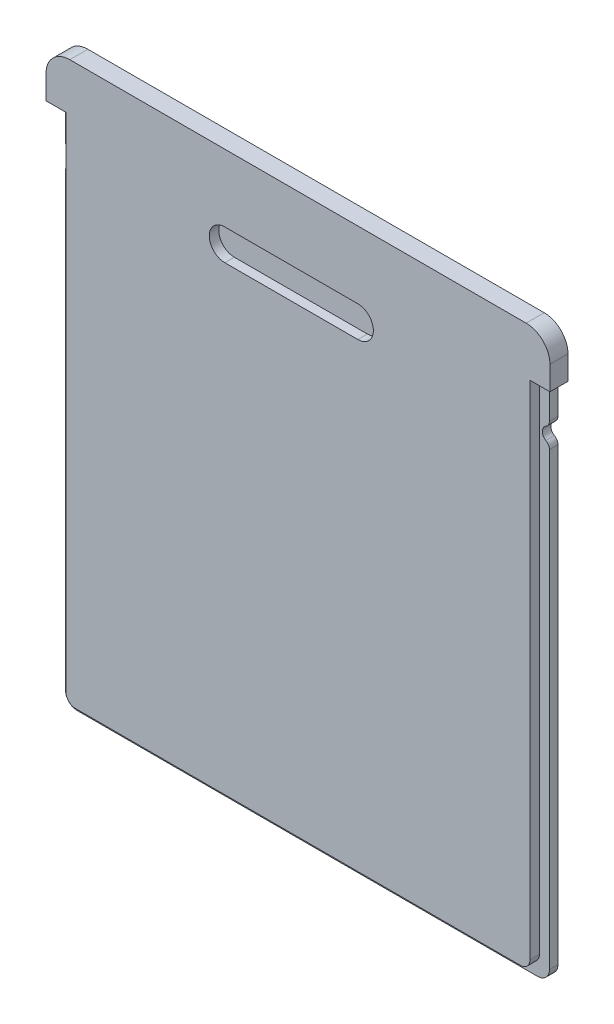
SolidWorks part; units mm, degrees
ref_plane "Front Plane" through (0, 0, 0) normal (0, 0, 1) x (1, 0, 0)
ref_plane "Top Plane" through (0, 0, 0) normal (0, 1, 0) x (1, 0, 0)
ref_plane "Right Plane" through (0, 0, 0) normal (1, 0, 0) x (0, 0, -1)
sketch "Sketch1" plane through (0, 0, 0) normal (0, 0, 1) x (1, 0, 0)
  line L0 (101.8, 109.8) -> (103.9, 109.8)
  line L1 (2.5, 0) -> (99.3, 0)
  line L2 (0, 2.5) -> (0, 109.8)
  line L4 (101.8, 2.5) -> (101.8, 109.8)
  line L5 (-2.1, 119.8) -> (103.9, 119.8)
  line L6 (-2.1, 119.8) -> (-2.1, 109.8)
  line L7 (-2.1, 109.8) -> (0, 109.8)
  line L8 (103.9, 119.8) -> (103.9, 109.8)
  arc A0 (99.3, 0) -> (101.8, 2.5) centre (99.3, 2.5) ccw
  arc A1 (2.5, 0) -> (0, 2.5) centre (2.5, 2.5) cw
  point P7 (101.8, 0)
  point P10 (0, 0)
  dimension "D3" = 2.5
  dimension "D1" = 101.8
  dimension "D2" = 119.8
  dimension "D4" = 106
  dimension "D5" = 2.1
  dimension "D6" = 10
extrude "Boss-Extrude1" add sketch "Sketch1" along normal blind 1.8
sketch "Sketch2" plane through (0, 0, 1.8) normal (0, 0, 1) x (1, 0, 0)
  line L2 (2.1, 109.8) -> (2.1, 4.2)
  line L3 (4.1, 2.2) -> (97.7, 2.2)
  line L4 (99.7, 109.8) -> (99.7, 4.2)
  line L5 (0, 109.8) -> (0, 2.5) construction
  line L6 (103.9, 119.8) -> (-2.1, 119.8) construction
  line L7 (101.8, 2.5) -> (101.8, 109.8) construction
  line L8 (2.5, 0) -> (99.3, 0) construction
  line L9 (-2.1, 119.8) -> (103.9, 119.8)
  line L11 (-2.1, 109.8) -> (2.1, 109.8)
  line L13 (99.7, 109.8) -> (103.9, 109.8)
  line L14 (-2.1, 119.8) -> (-2.1, 109.8) construction
  line L15 (-2.1, 119.8) -> (-2.1, 109.8)
  line L16 (103.9, 119.8) -> (103.9, 109.8)
  arc A0 (97.7, 2.2) -> (99.7, 4.2) centre (97.7, 4.2) ccw
  arc A1 (2.1, 4.2) -> (4.1, 2.2) centre (4.1, 4.2) ccw
  point P12 (99.7, 2.2)
  point P15 (2.1, 2.2)
  dimension "D5" = 2
  dimension "D1" = 2.2
  dimension "D2" = 2.1
  dimension "D4" = 2.1
extrude "Boss-Extrude2" add sketch "Sketch2" along normal blind 2 contours L2 A1 L3 A0 L4 L13 L16 L9 L15 L11
sketch "Sketch3" plane through (0, 0, 3.8) normal (0, 0, 1) x (1, 0, 0)
  line L0 (35.4969, 102.374) -> (63.5031, 102.374) construction
  line L1 (35.4969, 105.6306) -> (63.5031, 105.6306)
  line L2 (35.4969, 99.1175) -> (63.5031, 99.1175)
  line L4 (0, 109.8) -> (0, 2.5) construction
  arc A0 (35.4969, 105.6306) -> (35.4969, 99.1175) centre (35.4969, 102.374) ccw
  arc A1 (63.5031, 99.1175) -> (63.5031, 105.6306) centre (63.5031, 102.374) ccw
  point P2 (49.5, 102.374)
  dimension "D1" = 49.5
extrude "Cut-Extrude1" cut sketch "Sketch3" against normal blind 2
sketch "Sketch5" plane through (0, 0, 0) normal (0, 0, -1) x (-1, 0, 0)
  line L0 (-101.8, 2.5) -> (-101.8, 109.8) construction
  line L1 (0, 109.8) -> (0, 2.5) construction
  line L3 (-103.9, 119.8) -> (2.1, 119.8) construction
  circle A0 centre (-101.8, 99.8) radius 1.5
  circle A1 centre (0, 99.8) radius 1.5
  dimension "D1" = 3
  dimension "D2" = 3
  dimension "D3" = 20
  dimension "D4" = 20
extrude "Cut-Extrude2" cut sketch "Sketch5" against normal blind 1.8
fillet "Fillet3" radius 1.5 4 edges at (101.8, 98.3, 0.9) (101.8, 101.3, 0.9) (0, 101.3, 0.9) (0, 98.3, 0.9)
fillet "Fillet4" radius 5 2 edges at (-2.1, 119.8, 1.9) (103.9, 119.8, 1.9)
